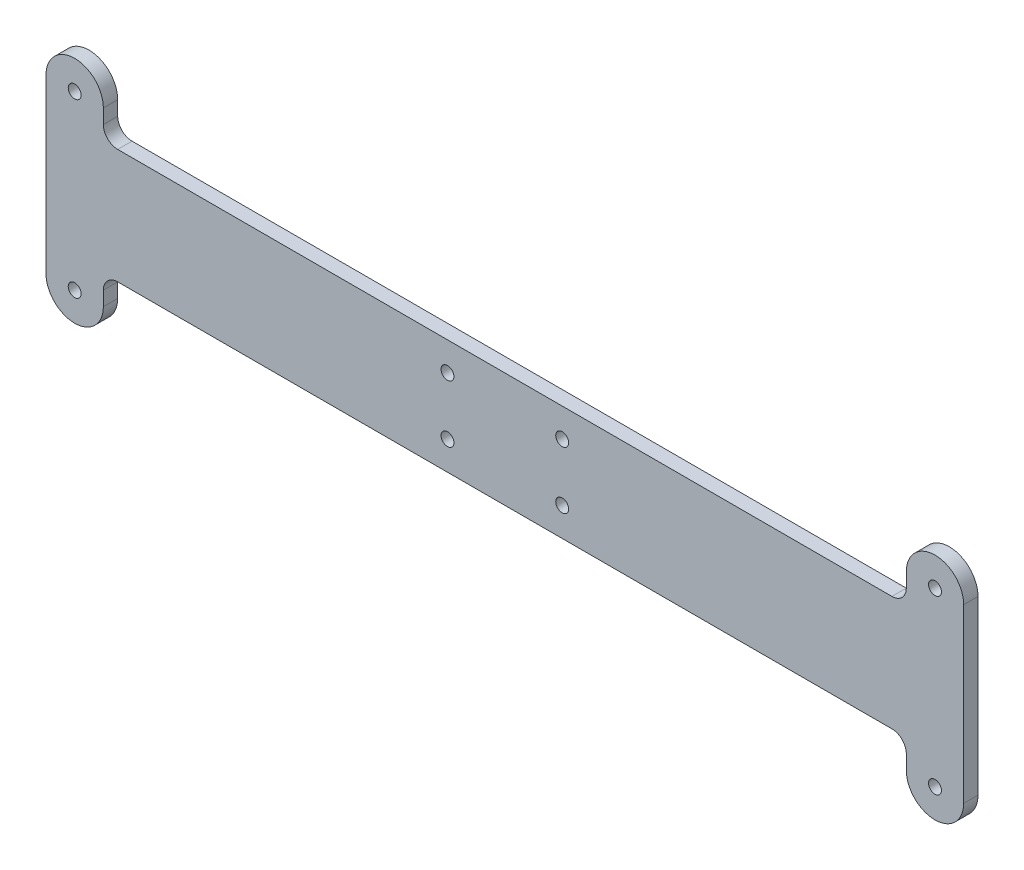
SolidWorks part; units mm, degrees
ref_plane "Plan de face" through (0, 0, 0) normal (0, 0, 1) x (1, 0, 0)
ref_plane "Plan de dessus" through (0, 0, 0) normal (0, 1, 0) x (1, 0, 0)
ref_plane "Plan de droite" through (0, 0, 0) normal (1, 0, 0) x (0, 0, -1)
sketch "Esquisse1" plane through (0, 0, 0) normal (0, 0, 1) x (1, 0, 0)
  line L0 (-135, 0) -> (135, 0)
  line L1 (140, -5) -> (140, -10)
  line L2 (160, -10) -> (160, 50)
  line L3 (0, 62.4131) -> (0, -5.9928) construction
  line L4 (177.3754, 20) -> (-176.3402, 20) construction
  line L5 (-160, -10) -> (-160, 50)
  line L6 (-140, -5) -> (-140, -10)
  line L7 (-140, 45) -> (-140, 50)
  line L8 (140, 45) -> (140, 50)
  line L9 (-135, 40) -> (135, 40)
  arc A0 (140, -10) -> (160, -10) centre (150, -10) ccw
  arc A1 (135, 0) -> (140, -5) centre (135, -5) cw
  arc A2 (-135, 0) -> (-140, -5) centre (-135, -5) ccw
  arc A3 (-140, -10) -> (-160, -10) centre (-150, -10) cw
  arc A4 (-140, 50) -> (-160, 50) centre (-150, 50) ccw
  arc A5 (-135, 40) -> (-140, 45) centre (-135, 45) cw
  arc A6 (135, 40) -> (140, 45) centre (135, 45) ccw
  arc A7 (140, 50) -> (160, 50) centre (150, 50) cw
  point P0 (-140, 0)
  point P8 (0, 40)
  point P17 (140, 0)
  point P25 (160, 20)
  point P26 (0, 0)
  point P41 (-160, 20)
  point P42 (140, 40)
  point P43 (-140, 40)
  dimension "D5" = 5
  dimension "D1" = 300
  dimension "D2" = 40
  dimension "D3" = 20
  dimension "D4" = 10
extrude "Boss.-Extru.1" add sketch "Esquisse1" along normal blind 5
hole_wizard "Dégagement M41" positions "Esquisse2" profile "Esquisse3" hole size "M4" standard "ISO" end condition through all
sketch "Esquisse2" plane through (0, 0, 0) normal (0, 0, -1) x (-1, 0, 0)
  point P0 (-150, -10)
  point P2 (150, 50)
  point P4 (150, -10)
  point P13 (-150, 50)
  point P15 (-150, 50)
  point P18 (-150, 50)
sketch "Esquisse3" plane through (150, -10, 0) normal (1, 0, 0) x (0, 1, 0)
  line L0 (0, 0) -> (0, 5)
  line L1 (0, 5) -> (2.25, 5)
  line L2 (2.25, 5) -> (2.25, 0)
  line L5 (2.25, 0) -> (0, 0)
  line L11 (0, -6.35) -> (0, 107.95) construction
  dimension "Diamètre du perçage jusqu'au prochain" = 4.5
  dimension "Profondeur du perçage jusqu'au prochain" = 5
hole_wizard "Dégagement M42" positions "Esquisse5" profile "Esquisse6" hole size "M4" standard "ISO" end condition through all
sketch "Esquisse5" plane through (0, 0, 0) normal (0, 0, -1) x (-1, 0, 0)
  line L0 (0, 0) -> (0, 40) construction
  line L1 (-135, 40) -> (135, 40) construction
  line L3 (-32.9252, 20) -> (32.9252, 20) construction
  point P0 (20, 10)
  point P15 (0, 20)
  point P16 (0, 20)
  point P17 (-20, 10)
  point P19 (-20, 30)
  point P21 (20, 30)
  point P24 (0, 0)
  point P25 (0, 0)
  point P26 (0, 0)
  dimension "D1" = 40
  dimension "D2" = 20
sketch "Esquisse6" plane through (-20, 10, 0) normal (1, 0, 0) x (0, 1, 0)
  line L0 (0, 0) -> (0, 5)
  line L1 (0, 5) -> (2.25, 5)
  line L2 (2.25, 5) -> (2.25, 0)
  line L5 (2.25, 0) -> (0, 0)
  line L11 (0, -6.35) -> (0, 107.95) construction
  dimension "Diamètre du perçage jusqu'au prochain" = 4.5
  dimension "Profondeur du perçage jusqu'au prochain" = 5
